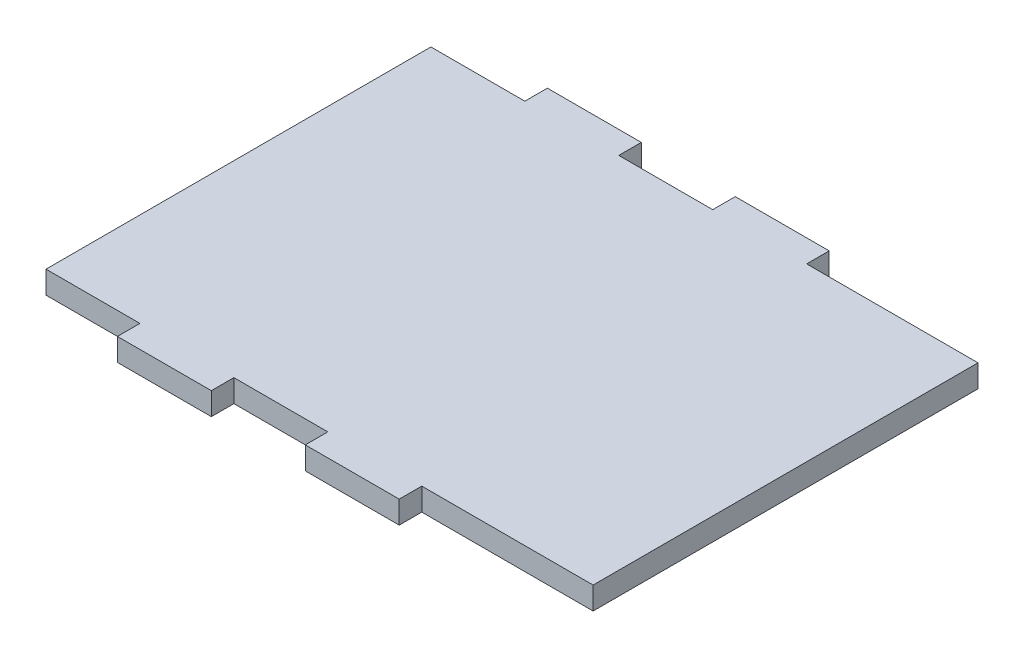
SolidWorks part; units mm, degrees
ref_plane "Спереди" through (0, 0, 0) normal (0, 0, 1) x (1, 0, 0)
ref_plane "Сверху" through (0, 0, 0) normal (0, 1, 0) x (1, 0, 0)
ref_plane "Справа" through (0, 0, 0) normal (1, 0, 0) x (0, 0, -1)
sketch "Эскиз1" plane through (0, 0, 0) normal (0, 1, 0) x (1, 0, 0)
  line L0 (-72.8, -66.2506) -> (-47.8, -66.2506) construction
  line L1 (27.2, -57.215) -> (27.2, -51.215)
  line L2 (-72.8, 51.215) -> (-72.8, -51.215)
  line L3 (-47.8, 51.215) -> (-72.8, 51.215)
  line L4 (72.8, 51.215) -> (72.8, -51.215)
  line L5 (-65.1656, 51.215) -> (65.1656, -51.215) construction
  line L6 (-65.1656, -51.215) -> (65.1656, 51.215) construction
  line L7 (-47.8, -57.215) -> (-47.8, -51.215)
  line L8 (-47.8, 57.215) -> (-22.8, 57.215)
  line L9 (-22.8, -51.215) -> (-22.8, -57.215)
  line L10 (-22.8, -66.2506) -> (2.2, -66.2506) construction
  line L11 (2.2, -57.215) -> (2.2, -51.215)
  line L12 (-22.8, 51.215) -> (2.2, 51.215)
  line L13 (2.2, 57.215) -> (27.2, 57.215)
  line L14 (27.2, -51.215) -> (72.8, -51.215)
  line L16 (-47.8, 57.215) -> (-47.8, 51.215)
  line L17 (27.2, 57.215) -> (27.2, 51.215)
  line L18 (-22.8, 51.215) -> (-22.8, 57.215)
  line L19 (2.2, 57.215) -> (2.2, 51.215)
  line L20 (27.2, 51.215) -> (72.8, 51.215)
  line L24 (-47.8, -51.215) -> (-72.8, -51.215)
  line L25 (-47.8, -57.215) -> (-22.8, -57.215)
  line L26 (2.2, -57.215) -> (27.2, -57.215)
  line L27 (2.2, -51.215) -> (-22.8, -51.215)
  point P0 (0, 0)
  dimension "D1" = 25
  dimension "D2" = 6
  dimension "D3" = 25
  dimension "D4" = 25
  dimension "D6" = 6
extrude "Бобышка-Вытянуть1" add sketch "Эскиз1" along normal blind 6
